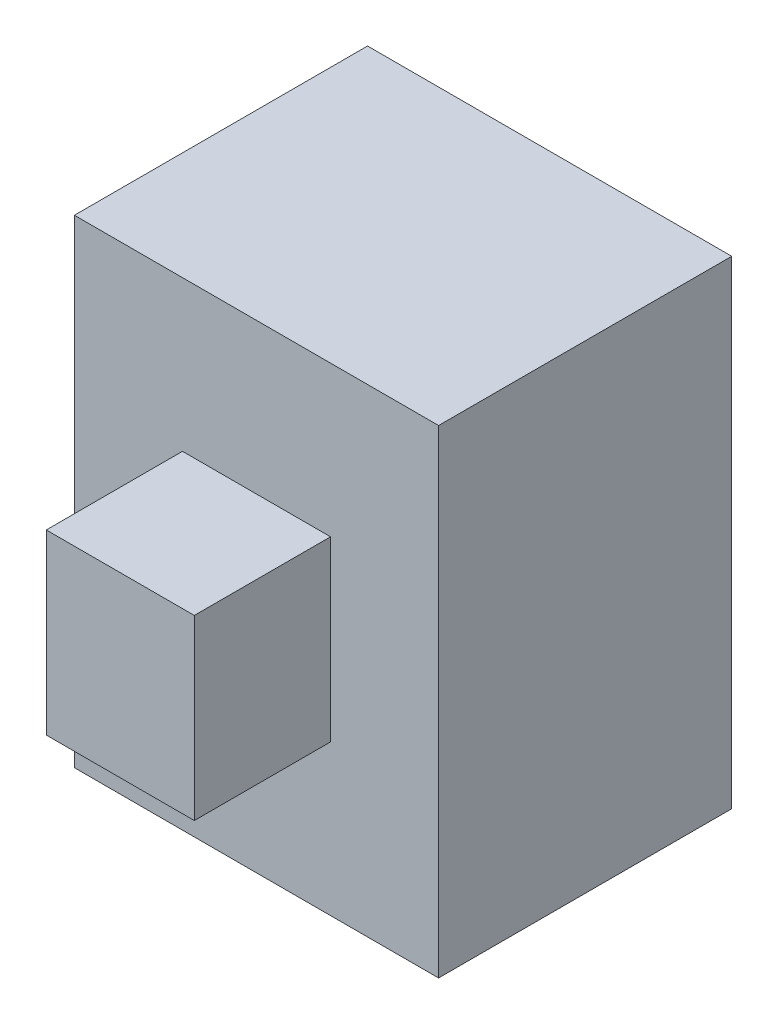
SolidWorks part; units mm, degrees
ref_plane "Front Plane" through (0, 0, 0) normal (0, 0, 1) x (1, 0, 0)
ref_plane "Top Plane" through (0, 0, 0) normal (0, 1, 0) x (1, 0, 0)
ref_plane "Right Plane" through (0, 0, 0) normal (1, 0, 0) x (0, 0, -1)
sketch "Sketch1" plane through (0, 0, 0) normal (0, 0, 1) x (1, 0, 0)
  line L1 (-7.8105, -10.2616) -> (7.8105, -10.2616)
  line L2 (-7.8105, -10.2616) -> (-7.8105, 10.2616)
  line L3 (-7.8105, 10.2616) -> (7.8105, 10.2616)
  line L4 (7.8105, -10.2616) -> (7.8105, 10.2616)
  line L5 (-7.8105, -10.2616) -> (7.8105, 10.2616) construction
  line L6 (-7.8105, 10.2616) -> (7.8105, -10.2616) construction
  point P0 (0, 0)
  dimension "D1" = 15.621
  dimension "D2" = 20.5232
extrude "Boss-Extrude1" add sketch "Sketch1" along normal blind 12.573 contours L3 L4 L1 L2
sketch "Sketch2" plane through (0, 0, 12.573) normal (0, 0, 1) x (1, 0, 0)
  line L1 (-3.175, 3.81) -> (3.175, 3.81)
  line L2 (-3.175, 3.81) -> (-3.175, -3.81)
  line L3 (-3.175, -3.81) -> (3.175, -3.81)
  line L4 (3.175, 3.81) -> (3.175, -3.81)
  line L5 (-3.175, 3.81) -> (3.175, -3.81) construction
  line L6 (-3.175, -3.81) -> (3.175, 3.81) construction
  line L8 (-7.8105, 10.2616) -> (7.8105, -10.2616) construction
  point P0 (0, 0)
  dimension "D1" = 6.35
  dimension "D2" = 7.62
extrude "Boss-Extrude2" add sketch "Sketch2" along normal blind 5.842
